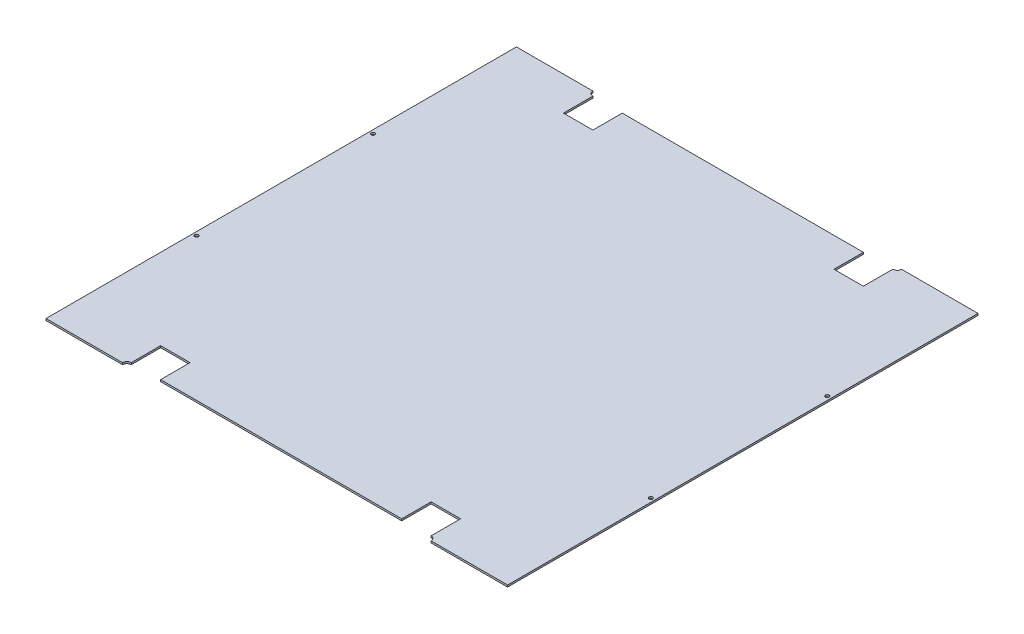
SolidWorks part; units mm, degrees
material "PC High Viscosity"
ref_plane "Front Plane" through (0, 0, 0) normal (0, 0, 1) x (1, 0, 0)
ref_plane "Top Plane" through (0, 0, 0) normal (0, 1, 0) x (1, 0, 0)
ref_plane "Right Plane" through (0, 0, 0) normal (1, 0, 0) x (0, 0, -1)
sketch "Sketch1" plane through (0, 0, 0) normal (0, 1, 0) x (1, 0, 0)
  line L0 (-132.5422, -200.1405) -> (126.5378, -200.1405) construction
  line L1 (-202.3922, 206.2595) -> (196.3878, 206.2595)
  line L2 (-202.3922, 206.2595) -> (-202.3922, -200.1405)
  line L3 (-202.3922, -200.1405) -> (196.3878, -200.1405)
  line L4 (196.3878, 206.2595) -> (196.3878, -200.1405)
  line L5 (-202.3922, 206.2595) -> (196.3878, -200.1405) construction
  line L7 (-132.5422, -196.3305) -> (126.5378, -196.3305)
  line L8 (-132.5422, -203.9505) -> (126.5378, -203.9505)
  line L16 (-132.5422, -170.9305) -> (-107.1422, -170.9305)
  line L17 (-132.5422, -170.9305) -> (-132.5422, -200.1405)
  line L18 (-132.5422, -200.1405) -> (-107.1422, -200.1405)
  line L19 (-107.1422, -170.9305) -> (-107.1422, -200.1405)
  line L22 (-132.5422, 206.2595) -> (126.5378, 206.2595) construction
  line L23 (-132.5422, 210.0695) -> (126.5378, 210.0695)
  line L24 (-132.5422, 202.4495) -> (126.5378, 202.4495)
  line L38 (101.1378, -170.9305) -> (126.5378, -170.9305)
  line L39 (101.1378, -170.9305) -> (101.1378, -200.1405)
  line L40 (101.1378, -200.1405) -> (126.5378, -200.1405)
  line L41 (126.5378, -170.9305) -> (126.5378, -200.1405)
  line L42 (-132.5422, 206.2595) -> (-107.1422, 206.2595)
  line L43 (-132.5422, 206.2595) -> (-132.5422, 177.0495)
  line L44 (-132.5422, 177.0495) -> (-107.1422, 177.0495)
  line L45 (-107.1422, 206.2595) -> (-107.1422, 177.0495)
  line L46 (101.1378, 206.2595) -> (126.5378, 206.2595)
  line L47 (101.1378, 206.2595) -> (101.1378, 177.0495)
  line L48 (101.1378, 177.0495) -> (126.5378, 177.0495)
  line L49 (126.5378, 206.2595) -> (126.5378, 177.0495)
  arc A0 (-132.5422, -196.3305) -> (-132.5422, -203.9505) centre (-132.5422, -200.1405) ccw
  arc A1 (126.5378, -203.9505) -> (126.5378, -196.3305) centre (126.5378, -200.1405) ccw
  arc A30 (-132.5422, 210.0695) -> (-132.5422, 202.4495) centre (-132.5422, 206.2595) ccw
  arc A31 (126.5378, 202.4495) -> (126.5378, 210.0695) centre (126.5378, 206.2595) ccw
  point P0 (0, 0)
  point P8 (-3.0022, -200.1405)
  point P13 (-3.0022, -200.1405)
  point P14 (-3.0022, -200.1405)
  point P27 (-199.2172, -73.1405)
  point P28 (193.2128, 79.2595)
  point P29 (193.2128, -73.1405)
  point P30 (-199.2172, 79.2595)
  point P85 (-3.0022, 206.2595)
  dimension "D4" = 3.81
  dimension "D9" = 3.175
  dimension "D11" = 152.4
  dimension "D17" = 29.21
  dimension "D18" = 69.85
  dimension "D6" = 69.85
  dimension "D24" = 29.21
  dimension "D29" = 3.81
  dimension "D1" = 398.78
  dimension "D2" = 406.4
  dimension "D3" = 69.85
  dimension "D5" = 0
  dimension "D7" = 152.4
  dimension "D8" = 127
  dimension "D10" = 3.175
  dimension "D12" = 127
  dimension "D13" = 3.175
  dimension "D14" = 3.175
  dimension "D16" = 25.4
  dimension "D19" = 25.4
  dimension "D20" = 29.21
  dimension "D21" = 69.85
  dimension "D22" = 69.85
  dimension "D23" = 0
  dimension "D25" = 25.4
  dimension "D26" = 69.85
  dimension "D27" = 25.4
  dimension "D28" = 29.21
  dimension "D15" = 69.85
extrude "Boss-Extrude1" add sketch "Sketch1" along normal blind 1.5875
hole_wizard "1/8 (0.125) Diameter Hole1" positions "Sketch4" profile "Sketch5" hole size "1/8" standard "ANSI Inch" end condition through all
sketch "Sketch4" plane through (0, 1.5875, 0) normal (0, 1, 0) x (1, 0, 0)
  point P0 (-199.2172, 79.2595)
  point P3 (-199.2172, -73.1405)
  point P6 (193.2128, -73.1405)
  point P9 (193.2128, 79.2595)
sketch "Sketch5" plane through (-199.2172, 1.5875, -79.2595) normal (1, 0, 0) x (0, 0, 1)
  line L0 (0, 0) -> (0, 1.5875)
  line L1 (0, 1.5875) -> (1.5875, 1.5875)
  line L2 (1.5875, 1.5875) -> (1.5875, 0)
  line L5 (1.5875, 0) -> (0, 0)
  line L11 (0, -6.35) -> (0, 107.95) construction
  dimension "Thru Hole Dia." = 3.175
  dimension "Thru Hole Depth" = 1.5875
